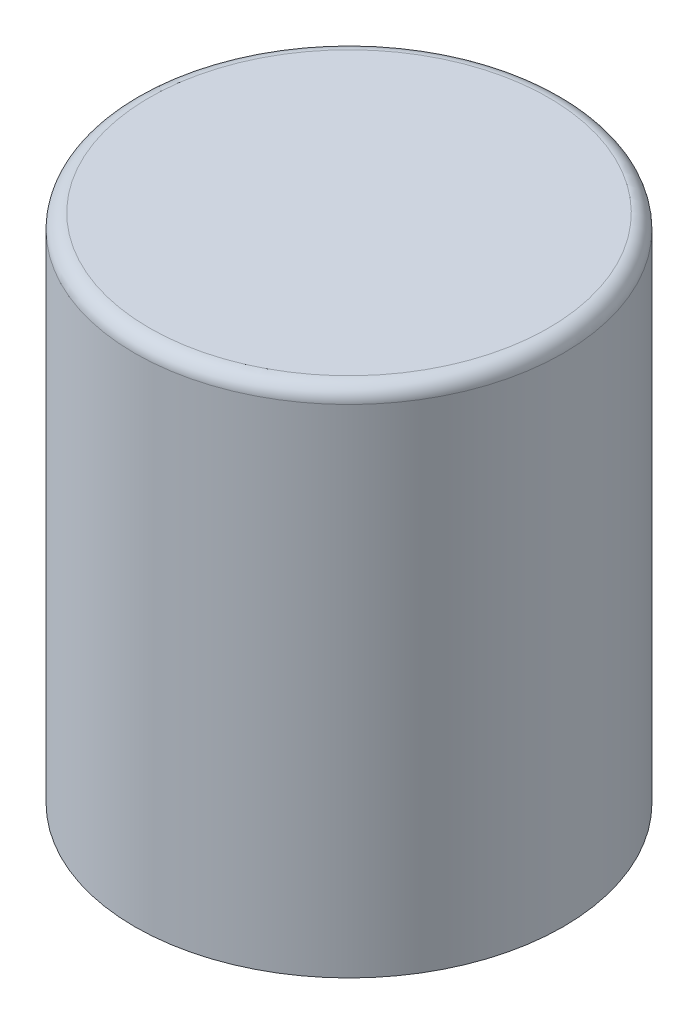
SolidWorks part; units mm, degrees
ref_plane "Front Plane" through (0, 0, 0) normal (0, 0, 1) x (1, 0, 0)
ref_plane "Top Plane" through (0, 0, 0) normal (0, 1, 0) x (1, 0, 0)
ref_plane "Right Plane" through (0, 0, 0) normal (1, 0, 0) x (0, 0, -1)
sketch "Sketch1" plane through (0, 0, 0) normal (0, 1, 0) x (1, 0, 0)
  circle A0 centre (0, 0) radius 4.4
  dimension "D1" = 8.8
extrude "Boss-Extrude1" add sketch "Sketch1" along normal blind 10.5
shell "Shell1" thickness 0.75
sketch "Sketch3" plane through (0, 9.75, 0) normal (0, -1, 0) x (1, 0, 0)
  line L0 (0, 3.65) -> (0, -3.65) construction
  line L2 (1.65, -1.65) -> (-1.65, -1.65)
  line L3 (1.65, -1.65) -> (1.65, 1.65)
  line L4 (1.65, 1.65) -> (-1.65, 1.65)
  line L5 (-1.65, -1.65) -> (-1.65, 1.65)
  line L6 (1.65, -1.65) -> (-1.65, 1.65) construction
  line L7 (1.65, 1.65) -> (-1.65, -1.65) construction
  line L8 (2.25, -2.25) -> (-2.25, -2.25)
  line L9 (2.25, -2.25) -> (2.25, 2.25)
  line L10 (2.25, 2.25) -> (-2.25, 2.25)
  line L11 (-2.25, -2.25) -> (-2.25, 2.25)
  line L12 (2.25, -2.25) -> (-2.25, 2.25) construction
  line L13 (2.25, 2.25) -> (-2.25, -2.25) construction
  circle A0 centre (0, 0) radius 3.65 construction
  circle A1 centre (0, 0) radius 3.65 construction
  point P7 (0, 0)
  point P12 (0, 0)
  dimension "D1" = 3.3
  dimension "D2" = 3.3
  dimension "D3" = 4.5
  dimension "D4" = 4.5
extrude "Boss-Extrude2" add sketch "Sketch3" along normal blind 9
sketch "Sketch5" plane through (0, 0.75, 0) normal (0, -1, 0) x (-1, 0, 0)
  line L0 (2.25, -2.25) -> (2.25, 2.25) construction
  line L1 (-2.25, 0.5) -> (2.25, 0.5)
  line L2 (-2.25, 0.5) -> (-2.25, -0.5)
  line L3 (-2.25, -0.5) -> (2.25, -0.5)
  line L4 (2.25, 0.5) -> (2.25, -0.5)
  line L5 (-2.25, 0.5) -> (2.25, -0.5) construction
  line L6 (-2.25, -0.5) -> (2.25, 0.5) construction
  point P0 (0, 0)
  dimension "D1" = 1
extrude "Cut-Extrude1" cut sketch "Sketch5" against normal blind 6.4
fillet "Fillet1" radius 0.3 1 edges at (0, 10.5, 4.4)
